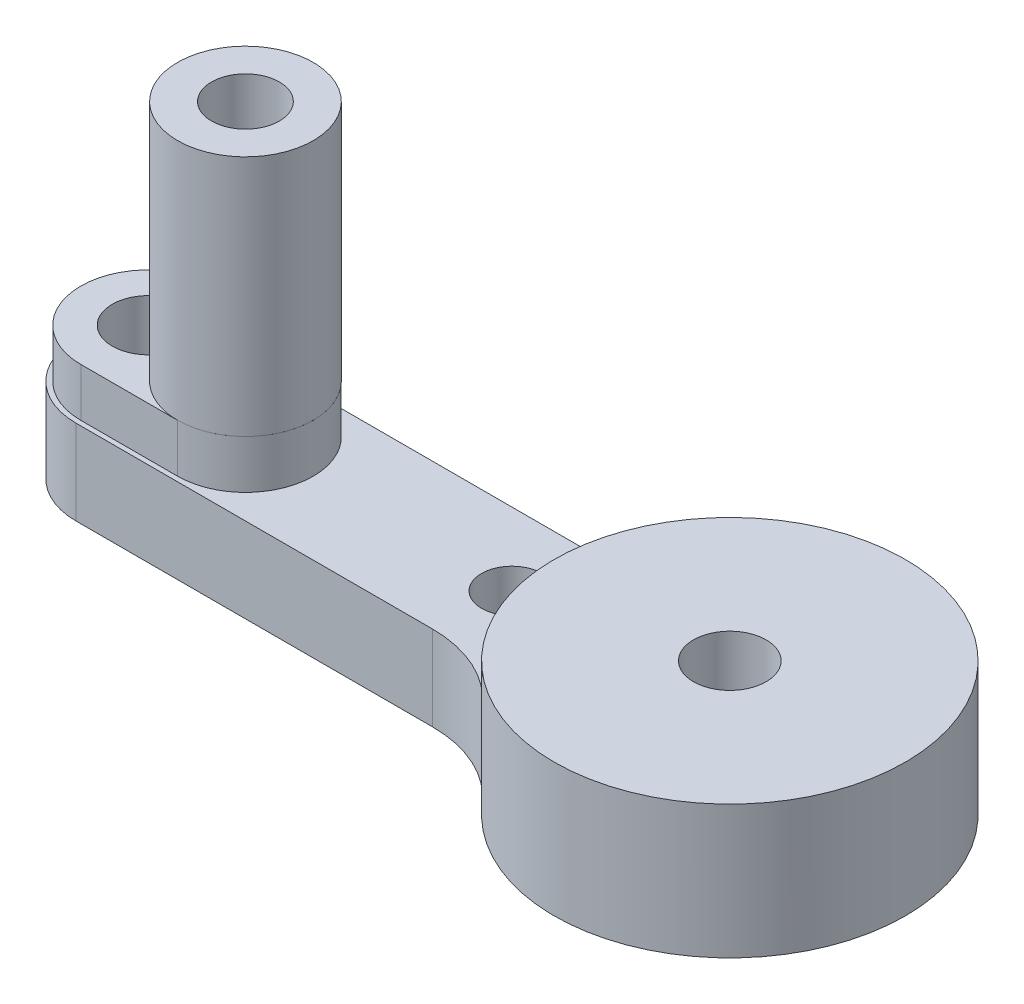
SolidWorks part; units mm, degrees
ref_plane "前视基准面" through (0, 0, 0) normal (0, 0, 1) x (1, 0, 0)
ref_plane "上视基准面" through (0, 0, 0) normal (0, 1, 0) x (1, 0, 0)
ref_plane "右视基准面" through (0, 0, 0) normal (1, 0, 0) x (0, 0, -1)
sketch "草图1" plane through (0, 0, 0) normal (0, 1, 0) x (1, 0, 0)
  line L0 (0, 0) -> (-22.2723, 0) construction
  line L1 (-24, -3) -> (-9.277, -3)
  line L2 (-24, 3) -> (-9.277, 3)
  arc A0 (-5.4905, -4.7347) -> (-5.4905, 4.7347) centre (0, 0) ccw
  circle A1 centre (0, 0) radius 1.5
  arc A2 (-24, 3) -> (-24, -3) centre (-24, 0) ccw
  circle A3 centre (-24, 0) radius 1.5
  circle A4 centre (-20, 0) radius 1.5
  circle A5 centre (-9, 0) radius 1.25
  arc A6 (-9.277, -3) -> (-5.4905, -4.7347) centre (-9.277, -8) cw
  arc A7 (-9.277, 3) -> (-5.4905, 4.7347) centre (-9.277, 8) ccw
  point P16 (-6.6002, -3)
  point P19 (-6.6002, 3)
  dimension "D1" = 14.5
  dimension "D2" = 3
  dimension "D5" = 3
  dimension "D6" = 4
  dimension "D7" = 2.5
  dimension "D8" = 9
  dimension "D9" = 5
  dimension "D3" = 6
  dimension "D4" = 24
extrude "凸台-拉伸1" add sketch "草图1" along normal blind 3.5
sketch "草图2" plane through (0, 3.5, 0) normal (0, 1, 0) x (1, 0, 0)
  line L0 (-9.277, 3) -> (-24, 3) construction
  line L1 (-24, 3) -> (-20, 3) construction
  line L2 (-20, -3) -> (-24, -3) construction
  line L3 (-24, 2.8) -> (-20, 2.8)
  line L4 (-20, -2.8) -> (-24, -2.8)
  circle A0 centre (0, 0) radius 7.25
  arc A1 (-5.4905, -4.7347) -> (-5.4905, 4.7347) centre (0, 0) ccw construction
  arc A3 (-20, -3) -> (-20, 3) centre (-20, 0) ccw construction
  arc A4 (-24, 3) -> (-24, -3) centre (-24, 0) ccw construction
  circle A6 centre (-24, 0) radius 1.5 construction
  circle A7 centre (-20, 0) radius 1.5 construction
  circle A8 centre (-20, 0) radius 1.5
  circle A9 centre (-24, 0) radius 1.5
  circle A11 centre (0, 0) radius 1.5 construction
  circle A12 centre (0, 0) radius 1.5
  arc A13 (-20, -2.8) -> (-20, 2.8) centre (-20, 0) ccw
  arc A14 (-24, 2.8) -> (-24, -2.8) centre (-24, 0) ccw
  dimension "D1" = 0.2
extrude "凸台-拉伸2" add sketch "草图2" along normal blind 2
sketch "草图5" plane through (0, 5.5, 0) normal (0, 1, 0) x (1, 0, 0)
  circle A0 centre (-20, 0) radius 1.4
  circle A2 centre (-20, 0) radius 2.8
  arc A3 (-20, -2.8) -> (-20, 2.8) centre (-20, 0) ccw construction
  dimension "D1" = 2.8
extrude "凸台-拉伸5" add sketch "草图5" along normal blind 10 separate body
